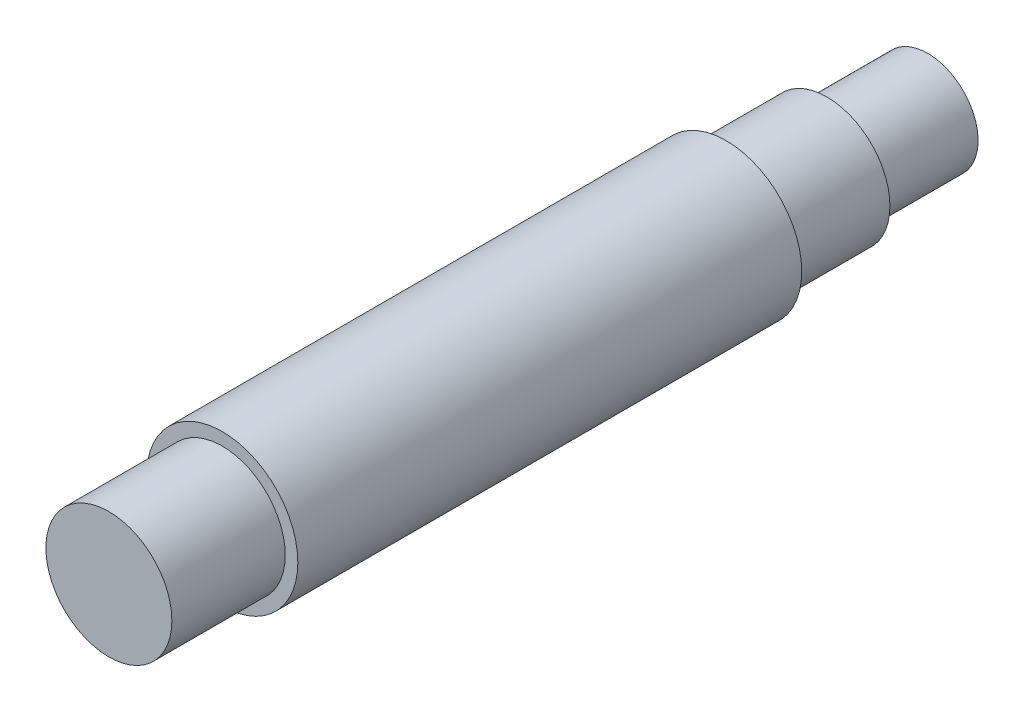
SolidWorks part; units mm, degrees
material "SKD11淬火HRC56-60"
ref_plane "前基準面" through (0, 0, 0) normal (0, 0, 1) x (1, 0, 0)
ref_plane "上基準面" through (0, 0, 0) normal (0, 1, 0) x (1, 0, 0)
ref_plane "右基準面" through (0, 0, 0) normal (1, 0, 0) x (0, 0, -1)
sketch "草图1" plane through (0, 0, 0) normal (0, 0, 1) x (1, 0, 0)
  circle A0 centre (0, 0) radius 6
  dimension "D1" = 12
extrude "凸台-拉伸1" add sketch "草图1" along normal blind 40
sketch "草图2" plane through (0, 0, 40) normal (0, 0, 1) x (1, 0, 0)
  circle A0 centre (0, 0) radius 5
  dimension "D1" = 10
extrude "凸台-拉伸2" add sketch "草图2" along normal blind 9
sketch "草图4" plane through (0, 0, 0) normal (0, 0, -1) x (-1, 0, 0)
  circle A0 centre (0, 0) radius 5
  dimension "D1" = 10
extrude "凸台-拉伸4" add sketch "草图4" along normal blind 8
sketch "草图6" plane through (0, 0, -8) normal (0, 0, -1) x (-1, 0, 0)
  circle A0 centre (0, 0) radius 4
  dimension "D1" = 8
extrude "凸台-拉伸6" add sketch "草图6" along normal blind 8
